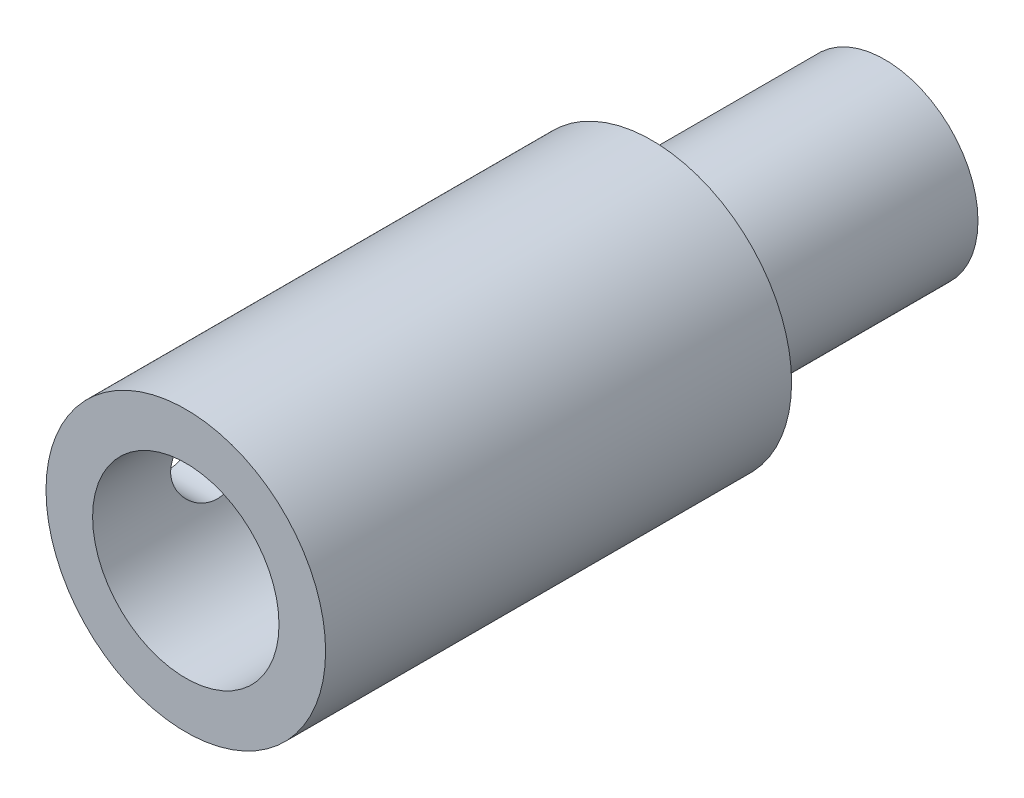
SolidWorks part; units mm, degrees
ref_plane "Front Plane" through (0, 0, 0) normal (0, 0, 1) x (1, 0, 0)
ref_plane "Top Plane" through (0, 0, 0) normal (0, 1, 0) x (1, 0, 0)
ref_plane "Right Plane" through (0, 0, 0) normal (1, 0, 0) x (0, 0, -1)
sketch "Sketch1" plane through (0, 0, 0) normal (0, 1, 0) x (1, 0, 0)
  line L0 (0, 6.35) -> (2.54, 6.35) construction
  line L1 (2.54, 6.35) -> (2.54, -6.35)
  line L2 (2.54, -6.35) -> (0, -6.35) construction
  line L3 (0, -6.35) -> (0, 6.35) construction
  line L4 (2.54, 6.35) -> (5.08, 6.35)
  line L5 (5.08, 6.35) -> (5.08, -6.35)
  line L7 (5.08, -6.35) -> (7.62, -6.35)
  line L8 (7.62, -6.35) -> (7.62, -31.75)
  line L9 (7.62, -31.75) -> (5.08, -31.75)
  line L10 (5.08, -31.75) -> (5.08, -8.89)
  line L11 (5.08, -8.89) -> (2.54, -8.89)
  line L12 (2.54, -8.89) -> (2.54, -6.35)
  point P13 (2.3111, -7.7332)
  point P14 (2.6773, -6.35)
  point P15 (7.62, -7.3396)
  point P16 (0, 0)
  dimension "D1" = 12.7
  dimension "D2" = 2.54
  dimension "D3" = 2.54
  dimension "D4" = 5.08
  dimension "D5" = 2.54
  dimension "D6" = 25.4
  dimension "D7" = 2.54
revolve "Revolve1" add sketch "Sketch1" angle 360 about L3
sketch "Sketch2" plane through (0, 0, -6.35) normal (0, 0, -1) x (-1, 0, 0)
  line L0 (1.651, -1.9302) -> (1.651, 1.9302)
  line L1 (-1.651, -1.9302) -> (-1.651, 1.9302)
  circle A0 centre (0, 0) radius 2.54 construction
  arc A1 (1.651, -1.9302) -> (1.651, 1.9302) centre (0, 0) ccw
  arc A2 (-1.651, 1.9302) -> (-1.651, -1.9302) centre (0, 0) ccw
  dimension "D1" = 3.302
extrude "Boss-Extrude1" add sketch "Sketch2" against normal up to surface (12.192 mm away) from offset 3.048 up to face at (5.08, 0, 8.89) offset against normal yes
sketch "Sketch4" plane through (0, 0, 0) normal (1, 0, 0) x (0, 0, -1)
  line L5 (-31.75, 7.62) -> (-31.75, -7.62) construction
  circle A0 centre (-25.4, 0) radius 2.0955
  point P2 (0, 0)
  point P5 (0, 0)
  dimension "D1" = 6.35
  dimension "D2" = 4.191
extrude "Cut-Extrude4" cut sketch "Sketch4" against normal blind 8.89 and the other way blind 6.35
